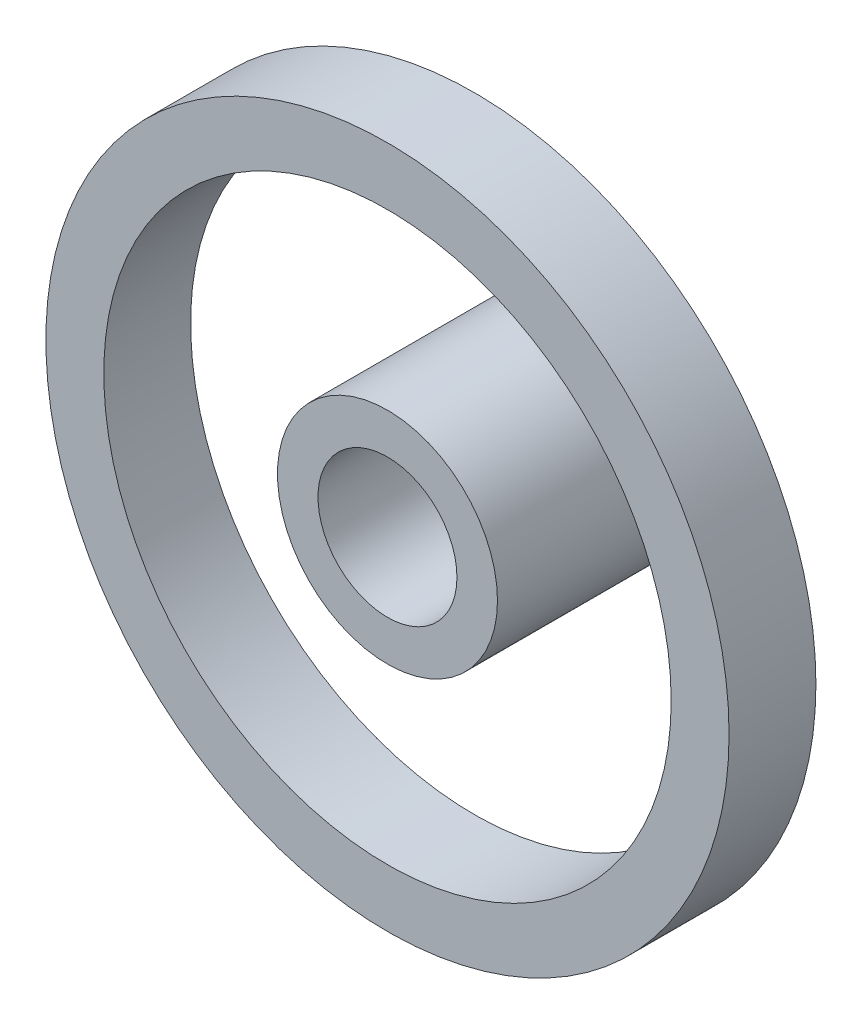
SolidWorks part; units mm, degrees
ref_plane "Front Plane" through (0, 0, 0) normal (0, 0, 1) x (1, 0, 0)
ref_plane "Top Plane" through (0, 0, 0) normal (0, 1, 0) x (1, 0, 0)
ref_plane "Right Plane" through (0, 0, 0) normal (1, 0, 0) x (0, 0, -1)
sketch "Sketch5" plane through (0, 0, 0) normal (0, 0, 1) x (1, 0, 0)
  circle A0 centre (0, 0) radius 1.2
  circle A1 centre (0, 0) radius 1.9
  dimension "D1" = 2.4
  dimension "D2" = 0.7
extrude "Boss-Extrude3" add sketch "Sketch5" along normal blind 3.5
sketch "Sketch7" plane through (0, 0, 3.5) normal (0, 0, 1) x (1, 0, 0)
  circle A1 centre (0, 0) radius 1.9
  circle A2 centre (0, 0) radius 1.9
  dimension "D1" = 0
sketch "Sketch8" plane through (0, 0, 3.5) normal (0, 0, 1) x (1, 0, 0)
  circle A0 centre (0, 0) radius 1.9 construction
  circle A1 centre (0, 0) radius 1.9
sketch "Sketch9" plane through (0, 0, 3.5) normal (0, 0, 1) x (1, 0, 0)
  circle A1 centre (0, 0) radius 5.9
  circle A2 centre (0, 0) radius 4.9
  circle A3 centre (0, 0) radius 4.9
  dimension "D1" = 3
  dimension "D2" = 1
extrude "Boss-Extrude4" add sketch "Sketch9" against normal blind 1.5 separate body
